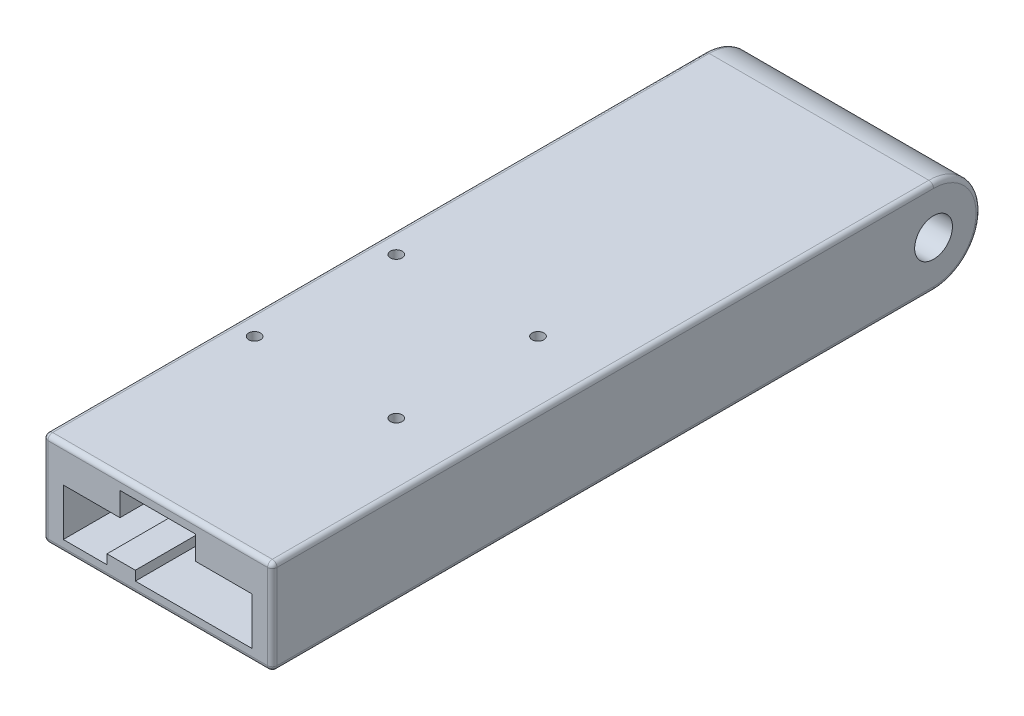
SolidWorks part; units mm, degrees
ref_plane "前视基准面" through (0, 0, 0) normal (0, 0, 1) x (1, 0, 0)
ref_plane "上视基准面" through (0, 0, 0) normal (0, 1, 0) x (1, 0, 0)
ref_plane "右视基准面" through (0, 0, 0) normal (1, 0, 0) x (0, 0, -1)
sketch "草图1" plane through (0, 0, 0) normal (0, 1, 0) x (1, 0, 0)
  line L1 (-24.25, 75) -> (24.25, 75)
  line L2 (-24.25, 75) -> (-24.25, -75)
  line L3 (-24.25, -75) -> (24.25, -75)
  line L4 (24.25, 75) -> (24.25, -75)
  line L5 (-24.25, 75) -> (24.25, -75) construction
  line L6 (-24.25, -75) -> (24.25, 75) construction
  point P0 (0, 0)
  dimension "D1" = 48.5
  dimension "D2" = 150
extrude "凸台-拉伸1" add sketch "草图1" along normal blind 20
sketch "草图3" plane through (24.25, 0, 0) normal (1, 0, 0) x (0, 0, -1)
  line L0 (65, 20) -> (65, 0) construction
  line L1 (-75, 20) -> (75, 20) construction
  line L2 (-75, 0) -> (75, 0) construction
  line L3 (75, 20) -> (75, 0) construction
  line L4 (65, 20) -> (75, 20)
  line L5 (75, 20) -> (75, 0)
  line L6 (75, 0) -> (65, 0)
  arc A0 (65, 20) -> (65, 0) centre (65, 10) cw
  point P8 (75, 10)
  line M1 (-75, 0) -> (75, 0)
  line M2 (75, 0) -> (75, 20)
  line M3 (75, 20) -> (-75, 20)
extrude "切除-拉伸1" cut sketch "草图3" against normal up to next contours A0 M2 M1 | A0 L5 M3
sketch "草图4" plane through (24.25, 0, 0) normal (1, 0, 0) x (0, 0, -1)
  line L0 (65, 20) -> (65, 0) construction
  circle A0 centre (65, 10) radius 4
  dimension "D1" = 8
extrude "切除-拉伸2" cut sketch "草图4" against normal up to next
sketch "草图5" plane through (0, 20, 0) normal (0, 1, 0) x (1, 0, 0)
  line L0 (0, 75) -> (0, -75) construction
  line L1 (24.25, 75) -> (-24.25, 75) construction
  line L2 (-24.25, -75) -> (24.25, -75) construction
  line L4 (-19.5, -5) -> (10.5, -5)
  line L5 (-19.5, -5) -> (-19.5, -35)
  line L6 (-19.5, -35) -> (10.5, -35)
  line L7 (10.5, -5) -> (10.5, -35)
  line L8 (-24.25, 65) -> (-24.25, -75) construction
  line L9 (-19.5, -5) -> (10.5, -35) construction
  dimension "D1" = 30
  dimension "D2" = 4.75
  dimension "D3" = 40
hole_wizard "M3x0.5 螺纹孔1" positions "3D草图1" profile "草图6" tap size "M3x0.5" standard "ANSI Metric"
sketch3d "3D草图1"
  point P0 (-19.5, 20, 5)
  point P3 (10.5, 20, 5)
  point P6 (-19.5, 20, 35)
  point P9 (10.5, 20, 35)
sketch "草图6" plane through (-19.5, 20, 5) normal (1, 0, 0) x (0, 0, 1)
  line L0 (0, 0) -> (0, 8.2511)
  line L1 (0, 8.2511) -> (1.25, 7.5)
  line L2 (1.25, 7.5) -> (1.25, 0)
  line L5 (1.25, 0) -> (0, 0)
  line L10 (0, 8.2511) -> (-1.25, 7.5) construction
  line L11 (0, -6.35) -> (0, 107.95) construction
  dimension "螺纹孔钻头直径" = 2.5
  dimension "螺纹孔钻头深度" = 7.5
  dimension "导头角度" = 118
cosmetic thread "孔螺蚊线1" parameters "D1"=6, "D2"=3
cosmetic thread "孔螺蚊线2" parameters "D1"=6, "D2"=3
cosmetic thread "孔螺蚊线3" parameters "D1"=6, "D2"=3
cosmetic thread "孔螺蚊线4" parameters "D1"=6, "D2"=3
sketch "草图9" plane through (-24.25, 0, 0) normal (-1, 0, 0) x (0, 0, 1)
  line L0 (24.1458, 0) -> (15.8542, 0)
  line L1 (24, 0) -> (16, 0) construction
  line L2 (-65, 0) -> (75, 0) construction
  arc A0 (24.1458, 0) -> (15.8542, 0) centre (20, -1.75) ccw
  dimension "D1" = 9
extrude "切除-拉伸3" cut sketch "草图9" against normal blind 14
sketch "草图10" plane through (-10.25, 0, 0) normal (-1, 0, 0) x (0, 0, 1)
  line L0 (28.8282, 0) -> (11.1718, 0)
  arc A0 (28.8282, 0) -> (11.1718, 0) centre (20, -1.75) ccw
  dimension "D1" = 18
extrude "切除-拉伸4" cut sketch "草图10" against normal blind 6 and the other way blind 1 contours A0 L0
sketch "草图11" plane through (0, 0, 75) normal (0, 0, 1) x (1, 0, 0)
  line L0 (-24.25, 0) -> (24.25, 20) construction
  line L1 (-4.7499, 0.4581) -> (-10.7499, 0.4581) construction
  line L2 (20, 2.5) -> (-20, 2.5)
  line L3 (20, 2.5) -> (20, 17.5)
  line L4 (20, 17.5) -> (-20, 17.5)
  line L5 (-20, 2.5) -> (-20, 17.5)
  line L6 (20, 2.5) -> (-20, 17.5) construction
  line L7 (20, 17.5) -> (-20, 2.5) construction
  line L8 (-26.65, -5.75) -> (-26.65, 2.25) construction
  line L9 (-26.65, -1.75) -> (-5.25, -1.75) construction
  line L10 (-4.7499, 4.5) -> (-10.7499, 4.5) construction
  line L11 (-10.7499, 4.5) -> (-10.7499, 0)
  line L12 (-24.25, 0) -> (24.25, 0) construction
  line L13 (-4.7499, 4.5) -> (-4.7499, 0)
  line L14 (-4.7499, 0) -> (-10.7499, 0)
  line L15 (-4.7499, 4.5) -> (-10.7499, 4.5)
  line L16 (-10.2499, 0.4581) -> (-5.2499, 0.4581) construction
  line L17 (8, 12.5) -> (8, 17.5)
  line L18 (8, 12.5) -> (20, 12.5)
  line L19 (20, 12.5) -> (20, 17.5)
  line L20 (20, 17.5) -> (8, 17.5)
  line L21 (0, 2.5) -> (0, 17.5) construction
  line L22 (-20, 12.5) -> (-20, 17.5)
  line L23 (-8, 12.5) -> (-20, 12.5)
  line L24 (-8, 12.5) -> (-8, 17.5)
  line L25 (-20, 17.5) -> (-8, 17.5)
  point P4 (0, 10)
  point P27 (-7.7499, 0.4581)
  dimension "D1" = 40
  dimension "D2" = 15
  dimension "D3" = 6
  dimension "D4" = 5
  dimension "D5" = 12
  dimension "D6" = 4.5
  dimension "D7" = 6
extrude "切除-拉伸5" cut sketch "草图11" against normal blind 120 contours L24 L23 L5 L2 L11 L15 L13 L3 L18 L17 L4
fillet "圆角1" radius 1 11 edges at (24.25, 10, -75) (-24.25, 10, -75) (24.25, 0, 5) (0, 0, 75) (24.25, 20, 5) (-24.25, 20, 5) (0, 20, 75) (24.25, 10, 75) (-24.25, 10, 75) (-24.25, 0, -24.5729) (-24.25, 0, 49.5729)
